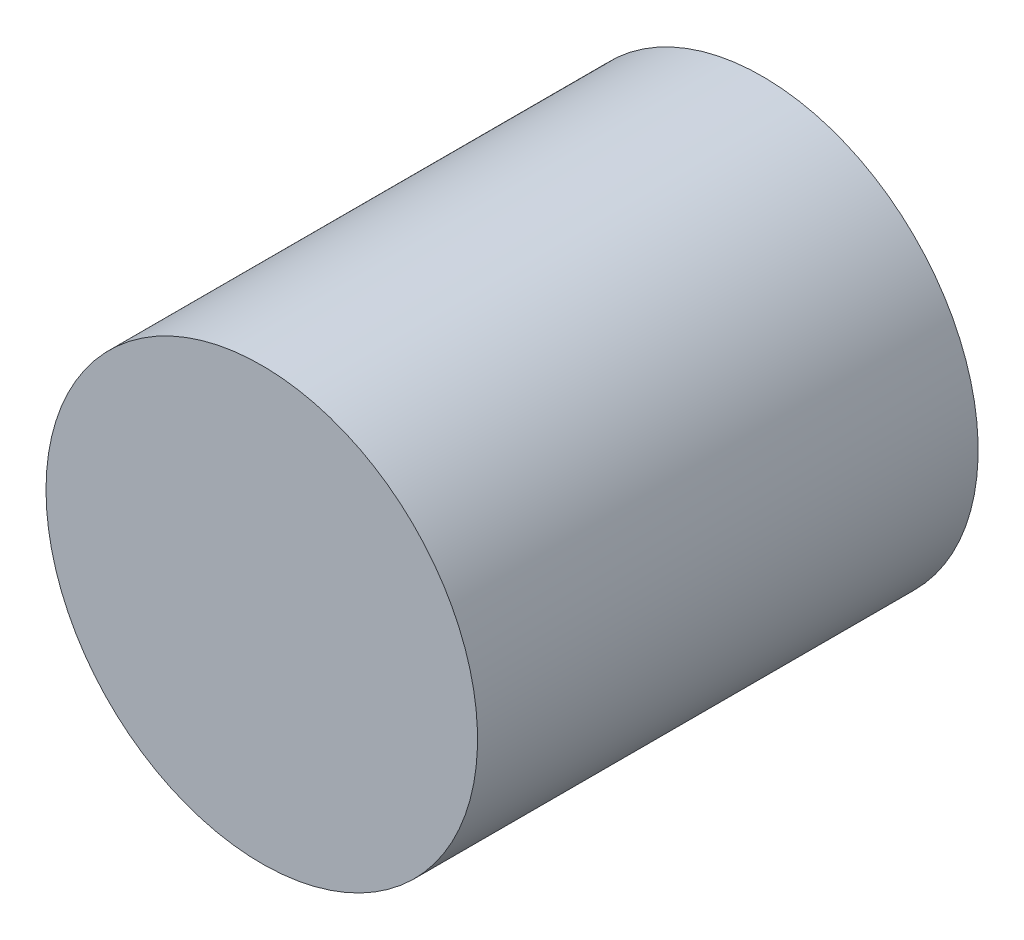
SolidWorks part; units mm, degrees
ref_plane "Front Plane" through (0, 0, 0) normal (0, 0, 1) x (1, 0, 0)
ref_plane "Top Plane" through (0, 0, 0) normal (0, 1, 0) x (1, 0, 0)
ref_plane "Right Plane" through (0, 0, 0) normal (1, 0, 0) x (0, 0, -1)
sketch "Sketch1" plane through (0, 0, 0) normal (0, 0, 1) x (1, 0, 0)
  circle A0 centre (0, 0) radius 12.5
  dimension "D1" = 25
extrude "Boss-Extrude1" add sketch "Sketch1" along normal blind 29
